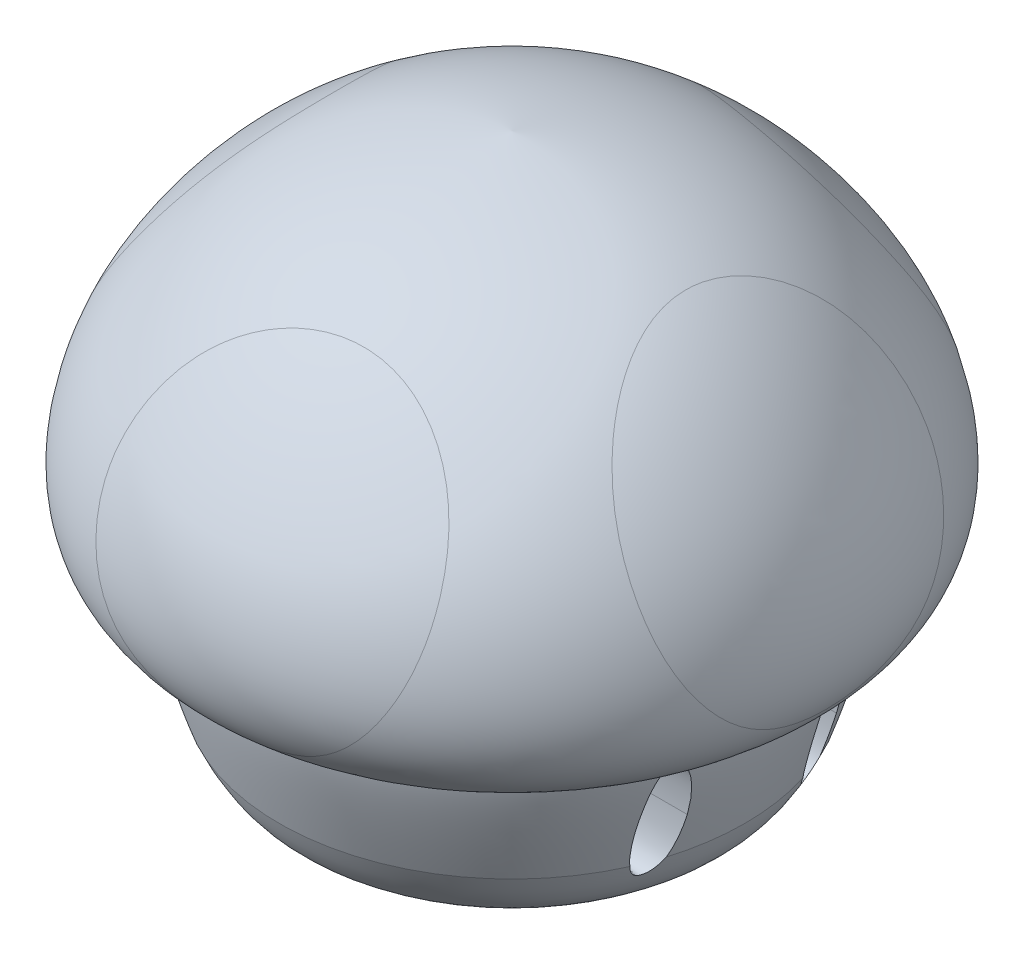
SolidWorks part; units mm, degrees
ref_plane "Plan de face" through (0, 0, 0) normal (0, 0, 1) x (1, 0, 0)
ref_plane "Plan de dessus" through (0, 0, 0) normal (0, 1, 0) x (1, 0, 0)
ref_plane "Plan de droite" through (0, 0, 0) normal (1, 0, 0) x (0, 0, -1)
sketch "Esquisse1" plane through (0, 0, 0) normal (0, 0, 1) x (1, 0, 0)
  line L2 (-136.8085, -132.6472) -> (-136.8085, 250.8119) construction
  line L3 (-136.8085, 199.2324) -> (-136.8085, -97.428)
  spline S1 degree 3 poles (0, 0) (14.825, -0.4458) (40.4788, 22.2704) (37.3692, 75.5098) (10.9361, 125.8373) (-44.0222, 181.3762) (-102.1843, 195.6072) (-136.8085, 199.2324) knots 0 0 0 0 0.131546 0.281325 0.463394 0.665748 1 1 1 1
  spline S2 degree 3 poles (-273.6171, 0) (-288.4421, -0.4458) (-314.0959, 22.2704) (-310.9863, 75.5098) (-284.5532, 125.8373) (-229.5949, 181.3762) (-171.4327, 195.6072) (-136.8085, 199.2324) knots 0 0 0 0 0.131546 0.281325 0.463394 0.665748 1 1 1 1
  spline S3 degree 2 poles (0, 0) (0.3859, -14.7678) (-13.4484, -56.5691) knots 0 0 0 1 1 1
  spline S4 degree 3 poles (-13.4484, -56.5691) (-23.7895, -79.0401) (-29.9318, -83.4054) (-48.1158, -91.6396) knots 0 0 0 0 1 1 1 1
  spline S5 degree 3 poles (-48.1158, -91.6396) (-81.1627, -98.263) (-103.2234, -95.2374) (-136.8085, -97.428) knots 0 0 0 0 1 1 1 1
  spline S6 degree 3 poles (-225.5013, -91.6396) (-192.4544, -98.263) (-170.3937, -95.2374) (-136.8085, -97.428) knots 0 0 0 0 1 1 1 1
  spline S7 degree 3 poles (-260.1687, -56.5691) (-249.8276, -79.0401) (-243.6853, -83.4054) (-225.5013, -91.6396) knots 0 0 0 0 1 1 1 1
  spline S8 degree 2 poles (-273.6171, 0) (-274.003, -14.7678) (-260.1687, -56.5691) knots 0 0 0 1 1 1
revolve "Révolution7" add sketch "Esquisse1" angle 360 about L3
sketch3d "Esquisse3D5"
  circle A0 centre (-120.0642, 86.6829, -0.8404) radius 77.5
  point P2 (-120.0642, 86.6829, 76.6596)
  point P3 (-120.0642, 86.6829, -0.8404)
  dimension "D1" = 155
split line "Ligne de séparation1"
ref_plane "Plan5" through (10, 0, 0) normal (1, 0, 0) x (0, 0, -1)
sketch "Esquisse7" plane through (10, 0, 0) normal (1, 0, 0) x (0, 0, -1)
  circle A0 centre (0, 95) radius 77.5
  point P2 (0, 95.309)
  dimension "D1" = 155
  dimension "D2" = 95
split line "Ligne de séparation9"
sketch "Esquisse8" plane through (10, 0, 0) normal (1, 0, 0) x (0, 0, -1)
  line L0 (0, 0) -> (0, -112.0878) construction
  spline S0 degree 3 poles (53.0208, -34.6921) (52.8572, -16.5202) (48.2929, -4.0826) (36.3776, -5.4709) (33.2243, -21.1177) (33.0208, -34.6921) knots 0 0 0 0 0.4069 0.5069 1 1 1 1
  spline S1 degree 3 poles (53.0208, -34.6921) (52.8572, -52.8639) (48.2929, -65.3015) (36.3776, -63.9132) (33.2243, -48.2664) (33.0208, -34.6921) knots 0 0 0 0 0.4069 0.5069 1 1 1 1
  spline S2 degree 3 poles (-53.0208, -34.6921) (-52.8572, -52.8639) (-48.2929, -65.3015) (-36.3776, -63.9132) (-33.2243, -48.2664) (-33.0208, -34.6921) knots 0 0 0 0 0.4069 0.5069 1 1 1 1
  spline S3 degree 3 poles (-53.0208, -34.6921) (-52.8572, -16.5202) (-48.2929, -4.0826) (-36.3776, -5.4709) (-33.2243, -21.1177) (-33.0208, -34.6921) knots 0 0 0 0 0.4069 0.5069 1 1 1 1
extrude "Enlèv. mat.-Extru.1" cut sketch "Esquisse8" against normal blind 60
